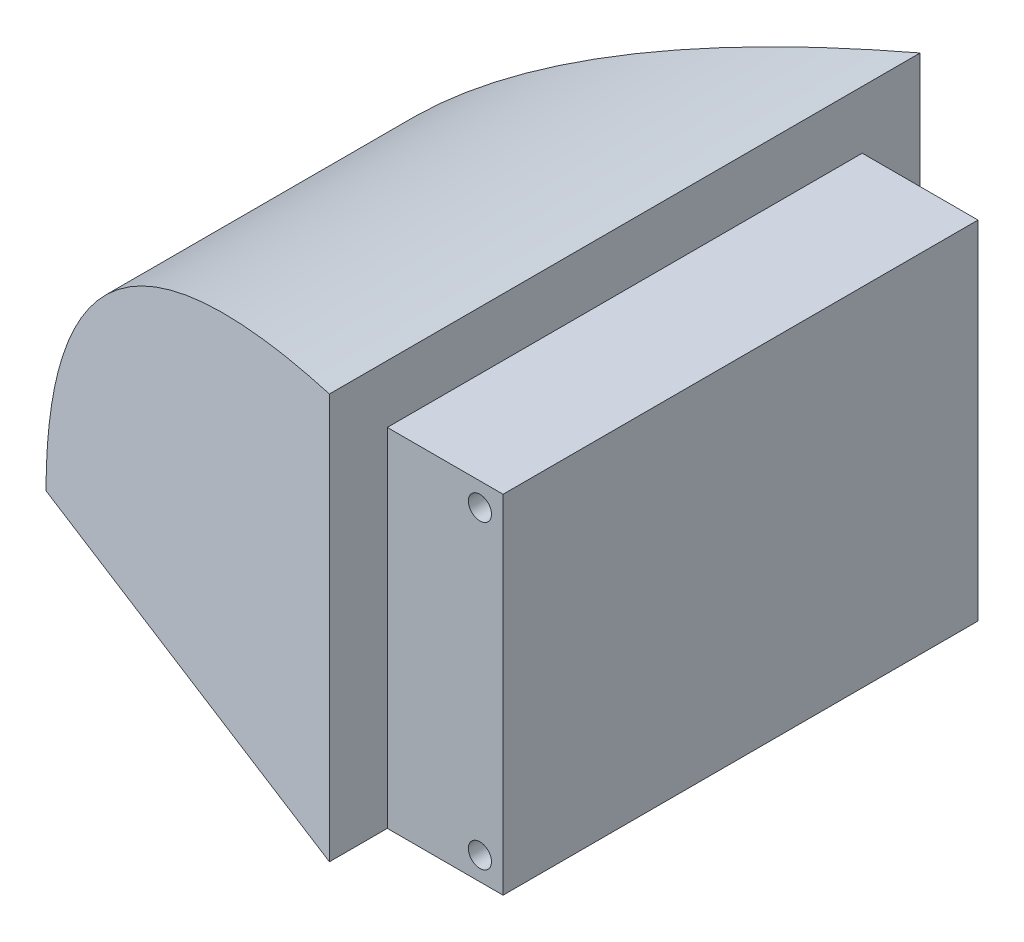
SolidWorks part; units mm, degrees
ref_plane "前视基准面" through (0, 0, 0) normal (0, 0, 1) x (1, 0, 0)
ref_plane "上视基准面" through (0, 0, 0) normal (0, 1, 0) x (1, 0, 0)
ref_plane "右视基准面" through (0, 0, 0) normal (1, 0, 0) x (0, 0, -1)
sketch "草图1" plane through (0, 0, 0) normal (0, 0, 1) x (1, 0, 0)
  line L0 (0, 0) -> (50000, 0) construction
  line L1 (0, 0) -> (0, 50000) construction
  line L3 (-25, 17.5) -> (25, 17.5)
  line L4 (-25, 17.5) -> (-25, -17.5)
  line L5 (-25, -17.5) -> (25, -17.5)
  line L6 (25, 17.5) -> (25, -17.5)
extrude "凸台-拉伸1" add sketch "草图1" along normal blind 51.03
sketch "草图2" plane through (0, 17.5, 0) normal (0, 1, 0) x (1, 0, 0)
  line L0 (-25, -25.515) -> (49975, -25.515) construction
  line L1 (-25, -51.03) -> (-25, 0) construction
  line L2 (0, -51.03) -> (0, 49948.97) construction
  line L3 (25, -51.03) -> (-25, -51.03) construction
  line L4 (25, -51.03) -> (25, 0) construction
  line L5 (15, -5) -> (25, -5)
  line L6 (15, -5) -> (15, -46.03)
  line L7 (15, -46.03) -> (25, -46.03)
  line L8 (25, -5) -> (25, -46.03)
  line L9 (25, 0) -> (-25, 0) construction
  line L11 (15, -5) -> (25, -5)
  line L12 (15, -5) -> (15, 0)
  line L13 (15, 0) -> (25, 0)
  line L14 (25, -5) -> (25, 0)
  line L15 (15, -46.03) -> (25, -46.03)
  line L16 (15, -46.03) -> (15, -51.03)
  line L17 (15, -51.03) -> (25, -51.03)
  line L18 (25, -46.03) -> (25, -51.03)
  point P4 (-25, -25.515)
  point P9 (0, -51.03)
  line M6 (25, 0) -> (-25, 0)
  line M8 (-25, -51.03) -> (25, -51.03)
  line M9 (25, -51.03) -> (25, 0)
  dimension "D1" = 5
  dimension "D2" = 10
extrude "切除-拉伸1" cut sketch "草图2" against normal blind 51.03 contours L12 L5 M9 M6 | L7 L16 M8 M9
sketch "草图3" plane through (0, 0, 51.03) normal (0, 0, 1) x (1, 0, 0)
  line L0 (15, 17.5) -> (-25, 17.5)
  line L1 (-25, 17.5) -> (-25, -17.5)
  spline S0 degree 2 poles (15, 17.5) (-25.0989, 8.9889) (-25, -17.7627) knots 0 0 0 1 1 1
  line M6 (15, 17.5) -> (-25, 17.5)
  line M7 (-25, 17.5) -> (-25, -17.5)
extrude "切除-拉伸16" cut sketch "草图3" against normal through all contours S0 M6 M7
sketch "草图11" plane through (0, -17.5, 0) normal (0, -1, 0) x (1, 0, 0)
  line L0 (-25, 25.515) -> (49975, 25.515) construction
  line L1 (-25, 51.03) -> (-25, 0) construction
  line L2 (-5, 51.03) -> (-5, -49948.97) construction
  line L3 (-25, 51.03) -> (15, 51.03) construction
  line L4 (15, 51.03) -> (-25, 35.515)
  line L5 (15, 0) -> (-25, 15.515)
  line L7 (15, 51.03) -> (-25, 51.03)
  line L8 (15, 51.03) -> (15, 0)
  line L9 (15, 0) -> (-25, 0)
  line L10 (-25, 51.03) -> (-25, 0)
  point P4 (-25, 25.515)
  point P9 (-5, 51.03)
  line M12 (15, 51.03) -> (-25, 51.03)
  line M13 (-25, 51.03) -> (-25, 0)
  line M14 (-25, 0) -> (15, 0)
  dimension "D1" = 20
extrude "切除-拉伸17" cut sketch "草图11" against normal through all contours L4 M12 M13 | L5 M14 M13
sketch "草图13" plane through (25, 0, 0) normal (1, 0, 0) x (0, 0, -1)
  line L0 (-5, -17.5) -> (-5, 17.5) construction
  line L1 (-46.03, 17.5) -> (-5, 17.5)
  line L2 (-46.03, 17.5) -> (-46.03, 12.5)
  line L3 (-46.03, 12.5) -> (-5, 12.5)
  line L4 (-5, 17.5) -> (-5, 12.5)
extrude "切除-拉伸18" cut sketch "草图13" against normal blind 10
sketch "草图14" plane through (0, 0, 46.03) normal (0, 0, 1) x (1, 0, 0)
  line L0 (25, -2.5) -> (50025, -2.5) construction
  line L1 (25, -17.5) -> (25, 12.5) construction
  line L2 (15, 12.5) -> (25, 12.5) construction
  circle A0 centre (23, 10.5) radius 1
  circle A1 centre (23, -15.5) radius 1
  point P8 (25, -2.5)
  dimension "D1" = 2
  dimension "D2" = 2
extrude "切除-拉伸19" cut sketch "草图14" against normal through all
